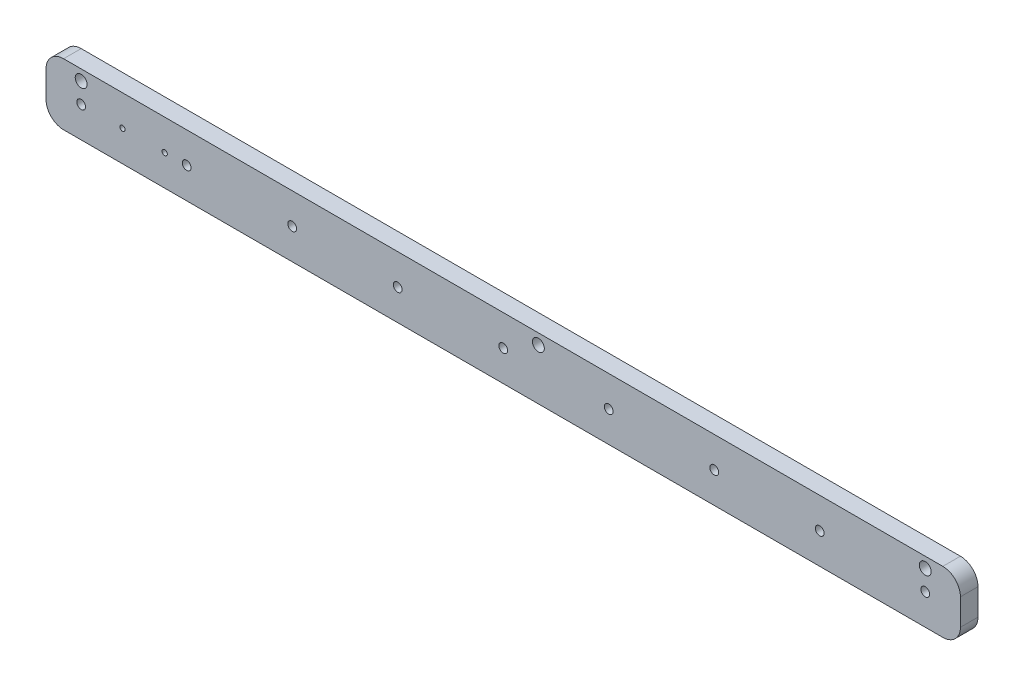
SolidWorks part; units mm, degrees
ref_plane "Plan de face" through (0, 0, 0) normal (0, 0, 1) x (1, 0, 0)
ref_plane "Plan de dessus" through (0, 0, 0) normal (0, 1, 0) x (1, 0, 0)
ref_plane "Plan de droite" through (0, 0, 0) normal (1, 0, 0) x (0, 0, -1)
sketch "Esquisse1" plane through (0, 0, 0) normal (0, 0, 1) x (1, 0, 0)
  line L0 (-280, 0) -> (-240, 0) construction
  line L1 (-250, 17.5) -> (250, 17.5)
  line L2 (-260, 7.5) -> (-260, -7.5)
  line L3 (-250, -17.5) -> (250, -17.5)
  line L4 (260, 7.5) -> (260, -7.5)
  line L5 (-260, 17.5) -> (260, -17.5) construction
  line L6 (-260, -17.5) -> (260, 17.5) construction
  circle A0 centre (-240, 0) radius 7
  circle A1 centre (-180, 0) radius 7
  circle A2 centre (-120, 0) radius 7
  circle A3 centre (-60, 0) radius 7
  circle A4 centre (0, 0) radius 7
  circle A5 centre (60, 0) radius 7
  circle A6 centre (120, 0) radius 7
  circle A7 centre (180, 0) radius 7
  circle A8 centre (240, 0) radius 7
  arc A9 (250, -17.5) -> (260, -7.5) centre (250, -7.5) ccw
  arc A10 (250, 17.5) -> (260, 7.5) centre (250, 7.5) cw
  arc A11 (-260, -7.5) -> (-250, -17.5) centre (-250, -7.5) ccw
  arc A12 (-250, 17.5) -> (-260, 7.5) centre (-250, 7.5) ccw
  point P0 (0, 0)
  point P11 (-260, 0)
  point P12 (-260, 0)
  dimension "D4" = 14
  dimension "D6" = 10
  dimension "D1" = 520
  dimension "D2" = 35
  dimension "D3" = 20
  dimension "D7" = 60
  dimension "D5" = 9
extrude "Boss.-Extru.1" add sketch "Esquisse1" along normal blind 10
sketch "Esquisse2" plane through (0, 0, 10) normal (0, 0, 1) x (1, 0, 0)
  circle A0 centre (-240, 0) radius 7 construction
  circle A1 centre (-240, 0) radius 7
  circle A2 centre (-180, 0) radius 7
  circle A3 centre (-120, 0) radius 7
  circle A4 centre (-60, 0) radius 7
  circle A5 centre (0, 0) radius 7
  circle A6 centre (60, 0) radius 7
  circle A7 centre (120, 0) radius 7
  circle A8 centre (180, 0) radius 7
  circle A9 centre (240, 0) radius 7
  circle A10 centre (-240, 0) radius 2.5
  circle A11 centre (-180, 0) radius 2.5
  circle A12 centre (-120, 0) radius 2.5
  circle A13 centre (-60, 0) radius 2.5
  circle A14 centre (0, 0) radius 2.5
  circle A15 centre (60, 0) radius 2.5
  circle A16 centre (120, 0) radius 2.5
  circle A17 centre (180, 0) radius 2.5
  circle A18 centre (240, 0) radius 2.5
  point P21 (0, 0)
  point P37 (0, 0)
  dimension "D2" = 9
  dimension "D3" = 5
  dimension "D4" = 60
  dimension "D1" = 9
extrude "Boss.-Extru.2" add sketch "Esquisse2" against normal blind 4
sketch "Esquisse3" plane through (0, 0, 10) normal (0, 0, 1) x (1, 0, 0)
  circle A0 centre (20, 11.5) radius 3.375
  circle A1 centre (-240, 11.5) radius 3.375
extrude "Enlèv. mat.-Extru.1" cut sketch "Esquisse3" against normal through all
sketch "Esquisse4" plane through (0, 0, 10) normal (0, 0, 1) x (1, 0, 0)
  circle A0 centre (240, 11.5) radius 3.375
extrude "Enlèv. mat.-Extru.2" cut sketch "Esquisse4" against normal through all
sketch "Esquisse5" plane through (0, 0, 10) normal (0, 0, 1) x (1, 0, 0)
  circle A0 centre (-192.5, 0) radius 1.5
  circle A1 centre (-216.5, 0) radius 1.5
extrude "Enlèv. mat.-Extru.3" cut sketch "Esquisse5" against normal through all
